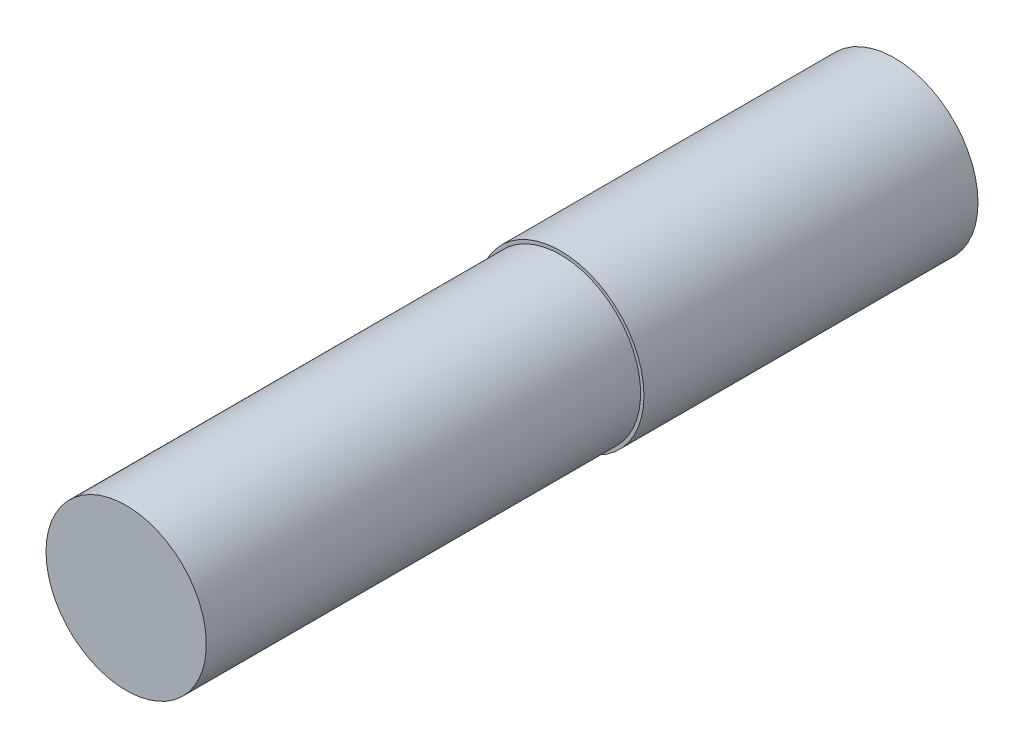
SolidWorks part; units mm, degrees
ref_plane "Plan de face" through (0, 0, 0) normal (0, 0, 1) x (1, 0, 0)
ref_plane "Plan de dessus" through (0, 0, 0) normal (0, 1, 0) x (1, 0, 0)
ref_plane "Plan de droite" through (0, 0, 0) normal (1, 0, 0) x (0, 0, -1)
sketch "Esquisse1" plane through (0, 0, 0) normal (0, 0, 1) x (1, 0, 0)
  circle A0 centre (0, 0) radius 2.5
  dimension "D1" = 5
extrude "Boss.-Extru.1" add sketch "Esquisse1" along normal blind 10
sketch "Esquisse2" plane through (0, 0, 10) normal (0, 0, 1) x (1, 0, 0)
  circle A0 centre (0, 0) radius 2.4
  dimension "D1" = 4.8
extrude "Boss.-Extru.2" add sketch "Esquisse2" along normal blind 13
